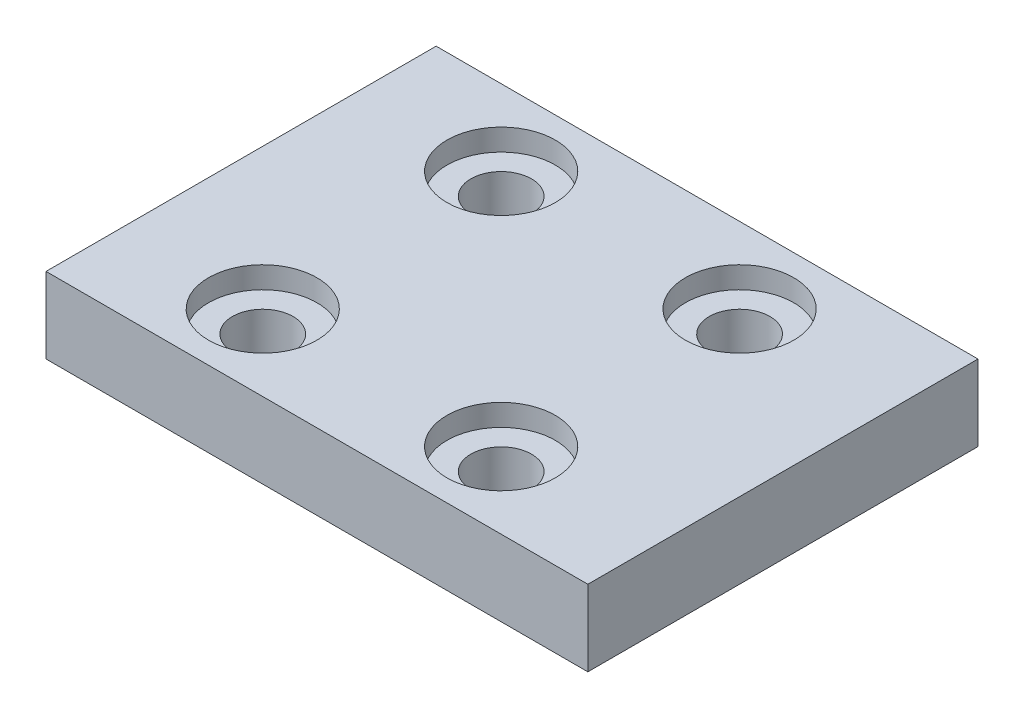
SolidWorks part; units mm, degrees
ref_plane "Front Plane" through (0, 0, 0) normal (0, 0, 1) x (1, 0, 0)
ref_plane "Top Plane" through (0, 0, 0) normal (0, 1, 0) x (1, 0, 0)
ref_plane "Right Plane" through (0, 0, 0) normal (1, 0, 0) x (0, 0, -1)
sketch "Sketch1" plane through (0, 0, 0) normal (0, 1, 0) x (1, 0, 0)
  line L1 (0, 0) -> (50, 0)
  line L2 (0, 0) -> (0, 36)
  line L3 (0, 36) -> (50, 36)
  line L4 (50, 0) -> (50, 36)
  dimension "D1" = 50
  dimension "D2" = 36
extrude "Boss-Extrude1" add sketch "Sketch1" along normal blind 7
sketch "Sketch2" plane through (0, 7, 0) normal (0, 1, 0) x (1, 0, 0)
  line L0 (0, 18) -> (50, 18) construction
  line L1 (0, 36) -> (0, 0) construction
  line L2 (50, 0) -> (50, 36) construction
  line L3 (25, 18) -> (25, 36) construction
  line L4 (50, 36) -> (0, 36) construction
  circle A0 centre (13, 29) radius 2.8
  circle A1 centre (13, 7) radius 2.8
  circle A4 centre (35, 29) radius 2.8
  circle A5 centre (35, 7) radius 2.8
  point P6 (25, 18)
  dimension "D1" = 11
  dimension "D2" = 5.6
  dimension "D4" = 22
  dimension "D3" = 13
extrude "Cut-Extrude1" cut sketch "Sketch2" against normal through all
sketch "Sketch3" plane through (0, 7, 0) normal (0, 1, 0) x (1, 0, 0)
  line L0 (25, 36) -> (25, 0) construction
  line L1 (50, 36) -> (0, 36) construction
  line L2 (0, 0) -> (50, 0) construction
  circle A0 centre (13, 29) radius 5
  circle A1 centre (13, 7) radius 5
  circle A4 centre (35, 29) radius 5
  circle A5 centre (35, 7) radius 5
  dimension "D1" = 10
extrude "Cut-Extrude2" cut sketch "Sketch3" against normal blind 2
